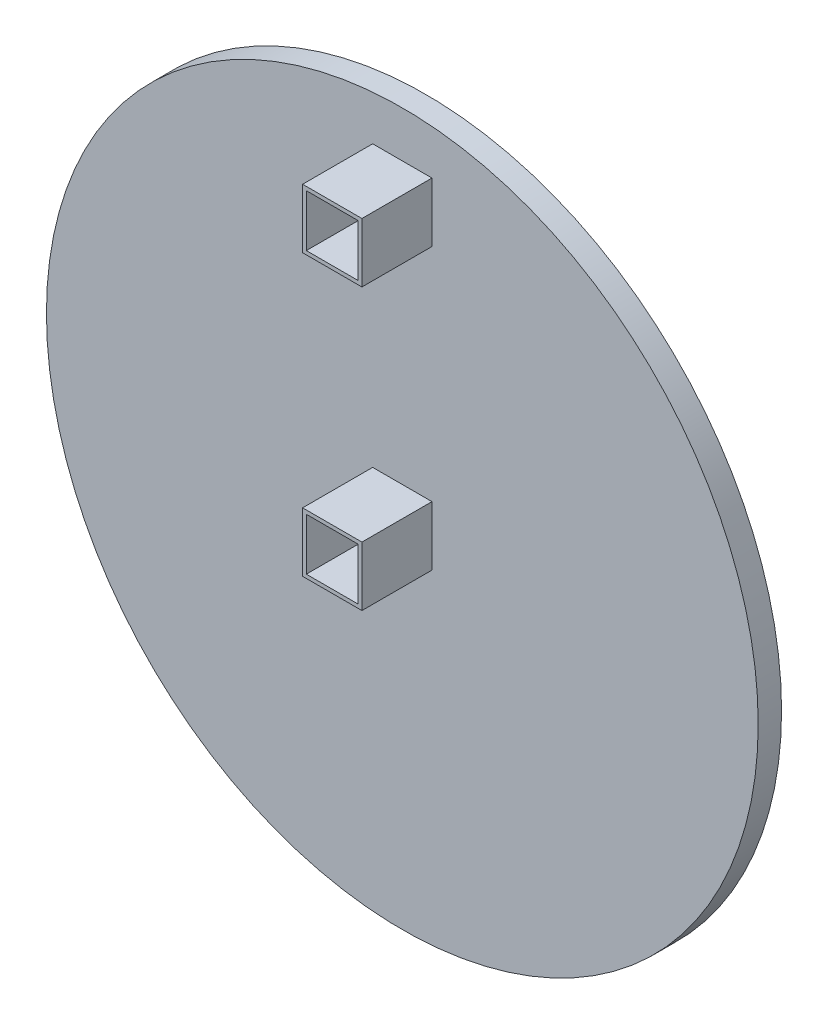
SolidWorks part; units mm, degrees
ref_plane "Front Plane" through (0, 0, 0) normal (0, 0, 1) x (1, 0, 0)
ref_plane "Top Plane" through (0, 0, 0) normal (0, 1, 0) x (1, 0, 0)
ref_plane "Right Plane" through (0, 0, 0) normal (1, 0, 0) x (0, 0, -1)
sketch "Sketch1" plane through (0, 0, 0) normal (0, 0, 1) x (1, 0, 0)
  circle A0 centre (0, 0) radius 152.4
  dimension "D1" = 304.8
extrude "Boss-Extrude1" add sketch "Sketch1" along normal blind 10
sketch "Sketch2" plane through (0, 0, 10) normal (0, 0, 1) x (1, 0, 0)
  line L1 (-12.7, 12.7) -> (12.7, 12.7)
  line L2 (-12.7, 12.7) -> (-12.7, -12.7)
  line L3 (-12.7, -12.7) -> (12.7, -12.7)
  line L4 (12.7, 12.7) -> (12.7, -12.7)
  line L5 (-12.7, 12.7) -> (12.7, -12.7) construction
  line L6 (-12.7, -12.7) -> (12.7, 12.7) construction
  line L7 (-11.1125, 11.1125) -> (11.1125, 11.1125)
  line L8 (-11.1125, 11.1125) -> (-11.1125, -11.1125)
  line L9 (-11.1125, -11.1125) -> (11.1125, -11.1125)
  line L10 (11.1125, 11.1125) -> (11.1125, -11.1125)
  line L11 (-11.1125, 11.1125) -> (11.1125, -11.1125) construction
  line L12 (-11.1125, -11.1125) -> (11.1125, 11.1125) construction
  line L25 (-12.7, 132.7) -> (12.7, 132.7)
  line L26 (-12.7, 132.7) -> (-12.7, 107.3)
  line L27 (-12.7, 107.3) -> (12.7, 107.3)
  line L28 (12.7, 132.7) -> (12.7, 107.3)
  line L29 (-12.7, 132.7) -> (12.7, 107.3) construction
  line L30 (-12.7, 107.3) -> (12.7, 132.7) construction
  line L31 (-11.1125, 131.1125) -> (11.1125, 131.1125)
  line L32 (-11.1125, 131.1125) -> (-11.1125, 108.8875)
  line L33 (-11.1125, 108.8875) -> (11.1125, 108.8875)
  line L34 (11.1125, 131.1125) -> (11.1125, 108.8875)
  line L35 (-11.1125, 131.1125) -> (11.1125, 108.8875) construction
  line L36 (-11.1125, 108.8875) -> (11.1125, 131.1125) construction
  point P0 (0, 0)
  point P6 (0, 0)
  point P22 (0, 120)
  point P27 (0, 120)
  dimension "D1" = 25.4
  dimension "D2" = 25.4
  dimension "D3" = 1.5875
  dimension "D7" = 25.4
  dimension "D8" = 25.4
  dimension "D9" = 1.5875
  dimension "D10" = 1.5875
  dimension "D11" = 120
extrude "Boss-Extrude2" add sketch "Sketch2" along normal blind 30
